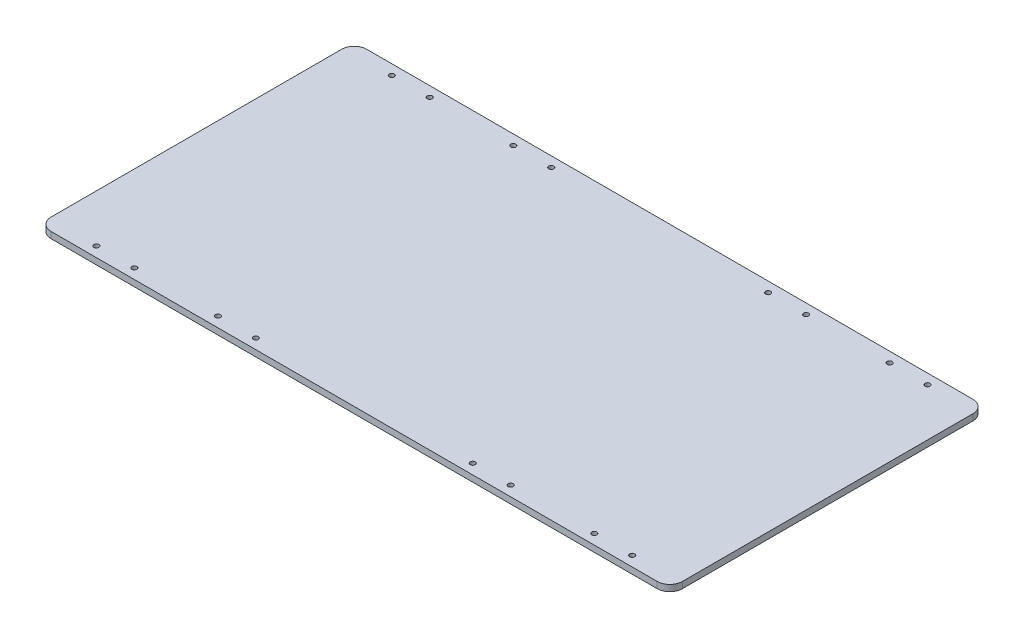
SolidWorks part; units mm, degrees
ref_plane "Alzado" through (0, 0, 0) normal (0, 0, 1) x (1, 0, 0)
ref_plane "Planta" through (0, 0, 0) normal (0, 1, 0) x (1, 0, 0)
ref_plane "Vista lateral" through (0, 0, 0) normal (1, 0, 0) x (0, 0, -1)
sketch "Croquis1" plane through (0, 0, 0) normal (0, 1, 0) x (1, 0, 0)
  line L1 (240, -125) -> (-240, -125)
  line L2 (250, -115) -> (250, 115)
  line L3 (240, 125) -> (-240, 125)
  line L4 (-250, -115) -> (-250, 115)
  line L5 (250, -125) -> (-250, 125) construction
  line L6 (250, 125) -> (-250, -125) construction
  arc A0 (250, 115) -> (240, 125) centre (240, 115) ccw
  arc A1 (240, -125) -> (250, -115) centre (240, -115) ccw
  arc A2 (-240, -125) -> (-250, -115) centre (-240, -115) cw
  arc A3 (-240, 125) -> (-250, 115) centre (-240, 115) ccw
  point P0 (0, 0)
  dimension "D3" = 10
  dimension "D1" = 250
  dimension "D2" = 500
extrude "Saliente-Extruir1" add sketch "Croquis1" along normal blind 5
sketch "Croquis2" plane through (0, 5, 0) normal (0, 1, 0) x (1, 0, 0)
  line L0 (-240, -125) -> (240, -125) construction
  line L1 (-250, 115) -> (-250, -115) construction
  line L2 (0, 125) -> (0, -125) construction
  line L3 (240, 125) -> (-240, 125) construction
  line L4 (-250, 0) -> (250, 0) construction
  line L5 (250, -115) -> (250, 115) construction
  circle A0 centre (-212.2, -116.98) radius 2
  circle A1 centre (-182.15, -116.98) radius 2
  circle A2 centre (-85.9, -116.98) radius 2
  circle A3 centre (-115.95, -116.98) radius 2
  circle A4 centre (212.2, -116.98) radius 2
  circle A5 centre (182.15, -116.98) radius 2
  circle A6 centre (115.95, -116.98) radius 2
  circle A7 centre (85.9, -116.98) radius 2
  circle A8 centre (212.2, 116.98) radius 2
  circle A9 centre (182.15, 116.98) radius 2
  circle A10 centre (115.95, 116.98) radius 2
  circle A11 centre (85.9, 116.98) radius 2
  circle A12 centre (-182.15, 116.98) radius 2
  circle A13 centre (-212.2, 116.98) radius 2
  circle A14 centre (-85.9, 116.98) radius 2
  circle A15 centre (-115.95, 116.98) radius 2
  dimension "D1" = 4
  dimension "D2" = 4
  dimension "D3" = 30.05
  dimension "D4" = 8.02
  dimension "D5" = 37.8
  dimension "D6" = 8.02
  dimension "D8" = 66.2
  dimension "D9" = 85.9
  dimension "D7" = 2
extrude "Cortar-Extruir1" cut sketch "Croquis2" against normal blind 10
